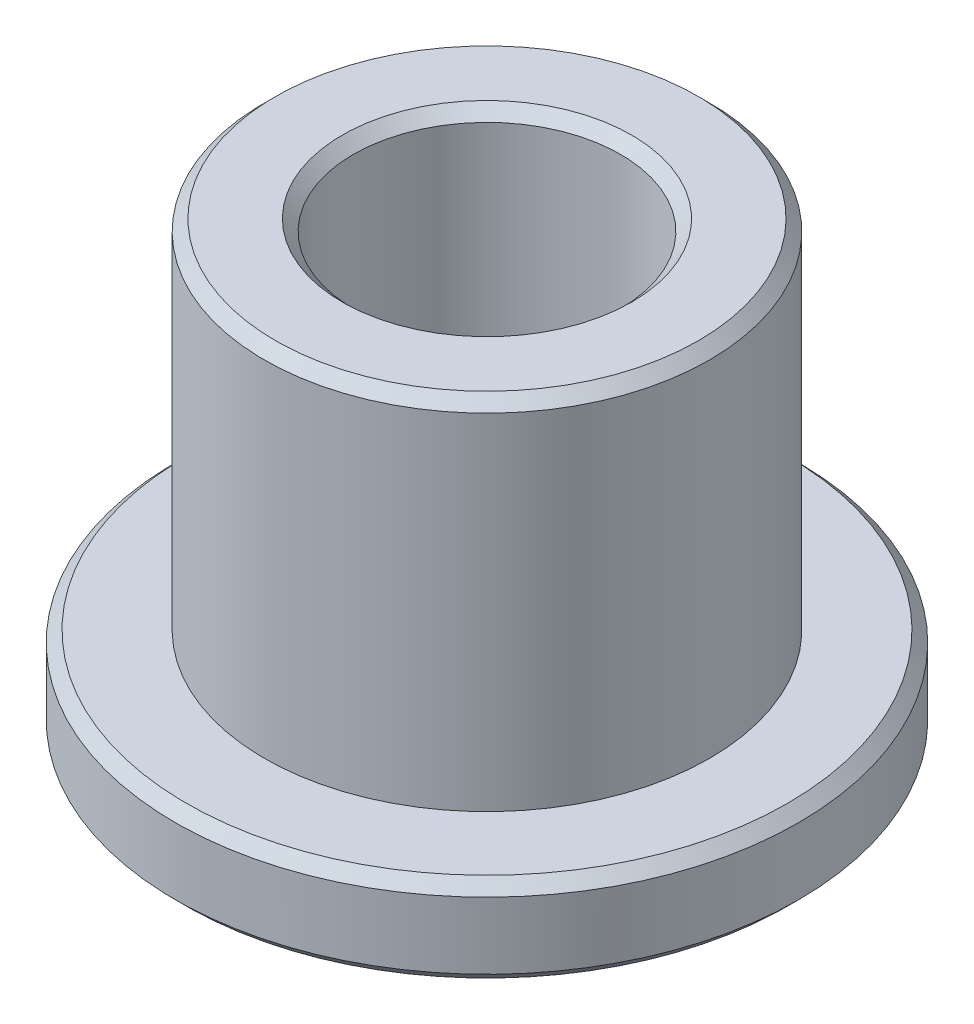
SolidWorks part; units mm, degrees
material "Brass"
ref_plane "Front Plane" through (0, 0, 0) normal (0, 0, 1) x (1, 0, 0)
ref_plane "Top Plane" through (0, 0, 0) normal (0, 1, 0) x (1, 0, 0)
ref_plane "Right Plane" through (0, 0, 0) normal (1, 0, 0) x (0, 0, -1)
sketch "Sketch1" plane through (0, 0, 0) normal (0, 0, 1) x (1, 0, 0)
  line L0 (0, -356.5588) -> (0, 17471.3836) construction
  line L1 (-3, 0) -> (-3, 10)
  line L2 (-3, 10) -> (-5, 10)
  line L3 (-5, 10) -> (-5, 2)
  line L4 (-5, 2) -> (-7, 2)
  line L5 (-7, 2) -> (-7, 0)
  line L6 (-7, 0) -> (-3, 0)
  dimension "D1" = 6
  dimension "D2" = 10
  dimension "D3" = 2
  dimension "D4" = 14
  dimension "D5" = 10
revolve "Revolve1" add sketch "Sketch1" angle 360 about L0
chamfer "Chamfer1" distance 0.25 angle 45 4 edges at (5, 10, 0) (3, 10, 0) (7, 0, 0) (7, 2, 0)
